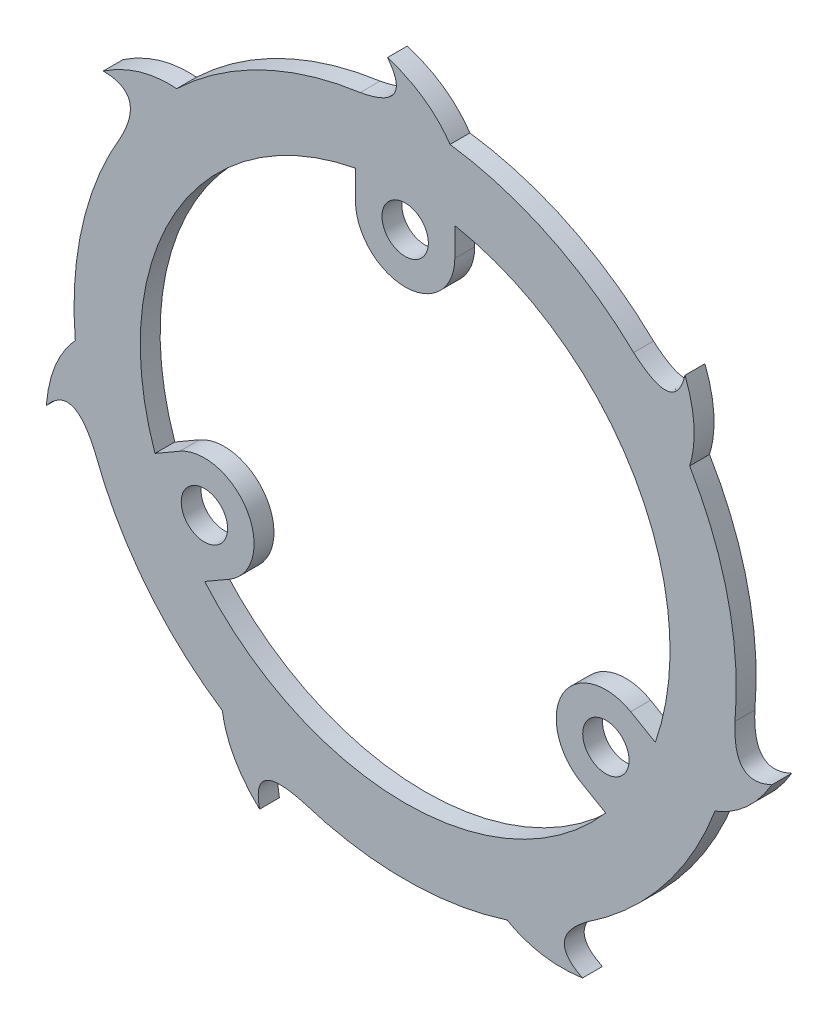
SolidWorks part; units mm, degrees
ref_plane "Front Plane" through (0, 0, 0) normal (0, 0, 1) x (1, 0, 0)
ref_plane "Top Plane" through (0, 0, 0) normal (0, 1, 0) x (1, 0, 0)
ref_plane "Right Plane" through (0, 0, 0) normal (1, 0, 0) x (0, 0, -1)
sketch "Sketch1" plane through (0, 0, 0) normal (0, 0, 1) x (1, 0, 0)
  line L0 (0, 0) -> (0, 17.78) construction
  line L1 (0, 17.78) -> (0, 20.32) construction
  line L2 (-3.81, 17.78) -> (-3.81, 19.9596)
  line L3 (3.81, 17.78) -> (3.81, 19.9596)
  line L8 (13.4929, -12.1896) -> (15.3805, -13.2794)
  line L9 (17.3029, -5.5904) -> (19.1905, -6.6803)
  line L12 (-17.3029, -5.5904) -> (-19.1905, -6.6803)
  line L13 (-13.4929, -12.1896) -> (-15.3805, -13.2794)
  circle A0 centre (0, 17.78) radius 1.778
  arc A1 (21.997, 12.7) -> (-21.997, 12.7) centre (0, 0) ccw
  arc A2 (-3.81, 19.9596) -> (-17.5976, 10.16) centre (0, 0) ccw
  arc A3 (-3.81, 17.78) -> (3.81, 17.78) centre (0, 17.78) ccw
  arc A5 (17.5976, 10.16) -> (3.81, 19.9596) centre (0, 0) ccw
  arc A6 (0, -25.4) -> (21.997, 12.7) centre (0, 0) ccw
  arc A7 (0, -20.32) -> (15.3805, -13.2794) centre (0, 0) ccw
  arc A8 (17.3029, -5.5904) -> (13.4929, -12.1896) centre (15.3979, -8.89) ccw
  arc A9 (19.1905, -6.6803) -> (17.5976, 10.16) centre (0, 0) ccw
  circle A10 centre (15.3979, -8.89) radius 1.778
  arc A11 (-21.997, 12.7) -> (0, -25.4) centre (0, 0) ccw
  arc A12 (-17.5976, 10.16) -> (-19.1905, -6.6803) centre (0, 0) ccw
  arc A13 (-13.4929, -12.1896) -> (-17.3029, -5.5904) centre (-15.3979, -8.89) ccw
  arc A14 (-15.3805, -13.2794) -> (0, -20.32) centre (0, 0) ccw
  circle A15 centre (-15.3979, -8.89) radius 1.778
  point P6 (0, 19.05)
  point P37 (0, 0)
  dimension "D1" = 17.78
  dimension "D2" = 3.556
  dimension "D3" = 50.8
  dimension "D4" = 40.64
  dimension "D7" = 3
extrude "Boss-Extrude1" add sketch "Sketch1" along normal blind 1.524
sketch "Sketch2" plane through (0, 0, 1.524) normal (0, 0, 1) x (1, 0, 0)
  line L0 (0, 25.4) -> (-1.3515, 28.543) construction
  line L1 (-1.3515, 28.543) -> (3.4442, 25.1654) construction
  line L2 (-3.4442, 25.1654) -> (4.3882, 23.3294)
  line L3 (17.5277, 18.3831) -> (20.9756, 11.1147)
  line L4 (19.8585, 15.8366) -> (21.4732, 18.8529) construction
  line L5 (21.4732, 18.8529) -> (21.8225, 12.9976) construction
  line L6 (25.3009, -2.242) -> (21.768, -9.4695)
  line L7 (24.7632, -5.652) -> (28.1281, -5.0338) construction
  line L8 (28.1281, -5.0338) -> (23.7681, -8.9577) construction
  line L9 (14.022, -21.1789) -> (6.1686, -22.923)
  line L10 (11.0206, -22.8846) -> (13.602, -25.13) construction
  line L11 (13.602, -25.13) -> (7.8158, -24.1676) construction
  line L12 (-7.8158, -24.1676) -> (-14.0759, -19.115)
  line L13 (-11.0206, -22.8846) -> (-11.1667, -26.3028) construction
  line L14 (-11.1667, -26.3028) -> (-14.022, -21.1789) construction
  line L15 (-23.7681, -8.9577) -> (-23.7209, -0.913)
  line L16 (-24.7632, -5.652) -> (-27.5267, -7.669) construction
  line L17 (-27.5267, -7.669) -> (-25.3009, -2.242) construction
  line L18 (-21.8225, 12.9976) -> (-15.5036, 17.9765)
  line L19 (-19.8585, 15.8366) -> (-23.1585, 16.7397) construction
  line L20 (-23.1585, 16.7397) -> (-17.5277, 18.3831) construction
  circle A0 centre (0, 0) radius 28.575 construction
  circle A1 centre (0, 0) radius 25.4 construction
  circle A2 centre (0, 0) radius 25.4
  spline S0 degree 1 poles (-0.6757, 26.9715) (0, 25.4) knots 0 0 1 1
  spline S1 degree 2 poles (-1.3515, 28.543) (0.6935, 25.9205) (-3.4442, 25.1654) knots 0 0 0 1 1 1
  spline S2 degree 2 poles (-1.3515, 28.543) (2.947, 27.1793) (4.3882, 23.3294) knots 0 0 0 1 1 1
  spline S3 degree 1 poles (20.6659, 17.3448) (19.8585, 15.8366) knots 0 0 1 1
  spline S4 degree 2 poles (21.4732, 18.8529) (20.6979, 15.619) (17.5277, 18.3831) knots 0 0 0 1 1 1
  spline S5 degree 2 poles (21.4732, 18.8529) (23.087, 14.6419) (20.9756, 11.1147) knots 0 0 0 1 1 1
  spline S6 degree 1 poles (26.4456, -5.3429) (24.7632, -5.652) knots 0 0 1 1
  spline S7 degree 2 poles (28.1281, -5.0338) (25.1163, -6.444) (25.3009, -2.242) knots 0 0 0 1 1 1
  spline S8 degree 2 poles (28.1281, -5.0338) (25.842, -8.9211) (21.768, -9.4695) knots 0 0 0 1 1 1
  spline S9 degree 1 poles (12.3113, -24.0073) (11.0206, -22.8846) knots 0 0 1 1
  spline S10 degree 2 poles (13.602, -25.13) (10.6217, -23.6545) (14.022, -21.1789) knots 0 0 0 1 1 1
  spline S11 degree 2 poles (13.602, -25.13) (9.1375, -25.7663) (6.1686, -22.923) knots 0 0 0 1 1 1
  spline S12 degree 1 poles (-11.0937, -24.5937) (-11.0206, -22.8846) knots 0 0 1 1
  spline S13 degree 2 poles (-11.1667, -26.3028) (-11.8713, -23.0527) (-7.8158, -24.1676) knots 0 0 0 1 1 1
  spline S14 degree 2 poles (-11.1667, -26.3028) (-14.4478, -23.209) (-14.0759, -19.115) knots 0 0 0 1 1 1
  spline S15 degree 1 poles (-26.1449, -6.6605) (-24.7632, -5.652) knots 0 0 1 1
  spline S16 degree 2 poles (-27.5267, -7.669) (-25.425, -5.0918) (-23.7681, -8.9577) knots 0 0 0 1 1 1
  spline S17 degree 2 poles (-27.5267, -7.669) (-27.1536, -3.1748) (-23.7209, -0.913) knots 0 0 0 1 1 1
  spline S18 degree 1 poles (-21.5085, 16.2882) (-19.8585, 15.8366) knots 0 0 1 1
  spline S19 degree 2 poles (-23.1585, 16.7397) (-19.8331, 16.7034) (-21.8225, 12.9976) knots 0 0 0 1 1 1
  spline S20 degree 2 poles (-23.1585, 16.7397) (-19.4122, 19.2501) (-15.5036, 17.9765) knots 0 0 0 1 1 1
  point P64 (0, 0)
  dimension "D1" = 57.15
  dimension "D2" = 7
extrude "Boss-Extrude2" add sketch "Sketch2" against normal up to surface (1.524 mm away) contours S2 L2 S1 | S5 L3 S4 | S8 L6 S7 | S11 L9 S10 | S14 L12 S13 | S17 L15 S16 | S20 L18 S19 up to face at (1.778, 17.78, 0)
